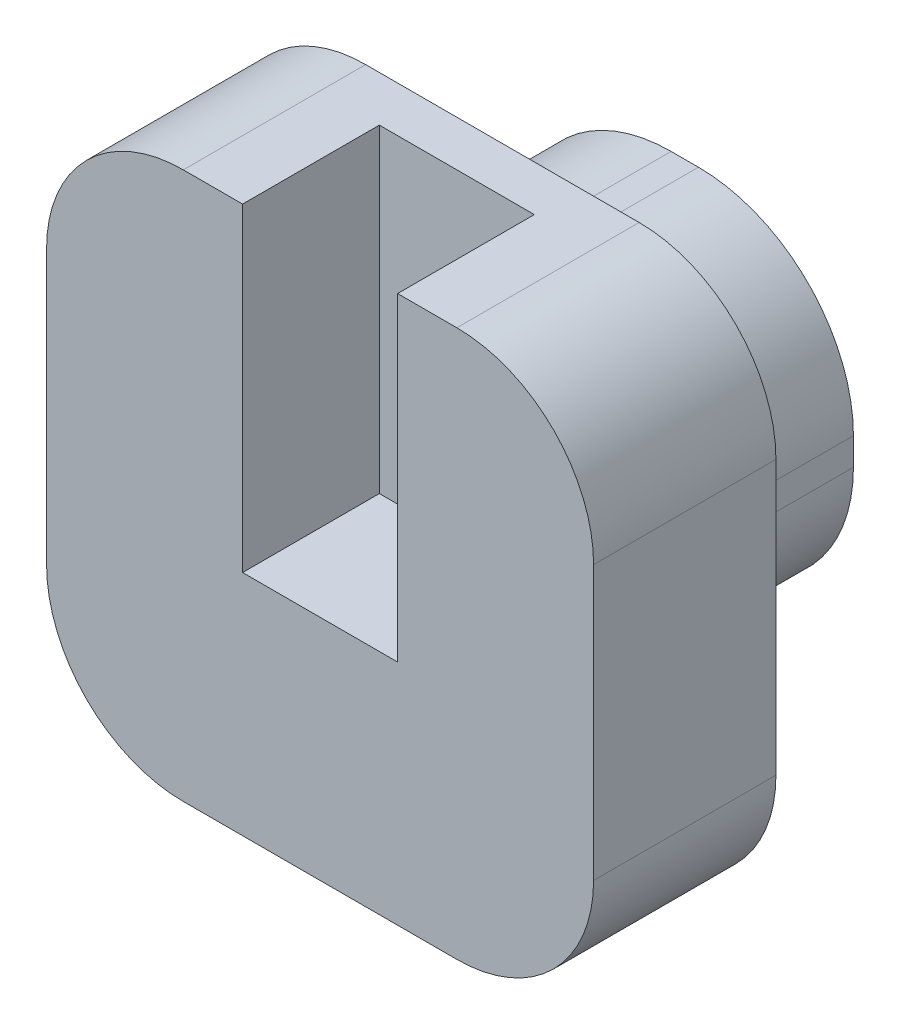
SolidWorks part; units mm, degrees
ref_plane "Спереди" through (0, 0, 0) normal (0, 0, 1) x (1, 0, 0)
ref_plane "Сверху" through (0, 0, 0) normal (0, 1, 0) x (1, 0, 0)
ref_plane "Справа" through (0, 0, 0) normal (1, 0, 0) x (0, 0, -1)
sketch "Эскиз1" plane through (0, 0, 0) normal (0, 0, 1) x (1, 0, 0)
  line L1 (-0.15, -1.85) -> (0.15, -1.85)
  line L2 (-1.85, -0.15) -> (-1.85, 0.15)
  line L3 (-0.15, 1.85) -> (0.15, 1.85)
  line L4 (1.85, -0.15) -> (1.85, 0.15)
  line L5 (-1.85, -1.85) -> (1.85, 1.85) construction
  line L6 (-1.85, 1.85) -> (1.85, -1.85) construction
  arc A0 (-1.85, -0.15) -> (-0.15, -1.85) centre (-0.15, -0.15) ccw
  arc A1 (1.85, 0.15) -> (0.15, 1.85) centre (0.15, 0.15) ccw
  arc A2 (-0.15, 1.85) -> (-1.85, 0.15) centre (-0.15, 0.15) ccw
  arc A3 (1.85, -0.15) -> (0.15, -1.85) centre (0.15, -0.15) cw
  point P0 (0, 0)
  dimension "D3" = 1.7
  dimension "D1" = 3.7
  dimension "D2" = 3.7
extrude "Бобышка-Вытянуть1" add sketch "Эскиз1" along normal blind 2
sketch "Эскиз2" plane through (0, 0, 2) normal (0, 0, 1) x (1, 0, 0)
  line L1 (-1.5, -3) -> (1.5, -3)
  line L2 (-3, -1.5) -> (-3, 1.5)
  line L3 (-1.5, 3) -> (1.5, 3)
  line L4 (3, -1.5) -> (3, 1.5)
  line L5 (-3, -3) -> (3, 3) construction
  line L6 (-3, 3) -> (3, -3) construction
  arc A0 (1.5, -3) -> (3, -1.5) centre (1.5, -1.5) ccw
  arc A1 (-1.5, -3) -> (-3, -1.5) centre (-1.5, -1.5) cw
  arc A2 (3, 1.5) -> (1.5, 3) centre (1.5, 1.5) ccw
  arc A3 (-3, 1.5) -> (-1.5, 3) centre (-1.5, 1.5) cw
  point P0 (0, 0)
  dimension "D3" = 1.5
  dimension "D1" = 6
  dimension "D2" = 6
extrude "Бобышка-Вытянуть2" add sketch "Эскиз2" along normal blind 2 contours A3 L2 A1 L1 A0 L4 A2 L3
sketch "Эскиз4" plane through (0, 3, 0) normal (0, 1, 0) x (1, 0, 0)
  line L0 (3, -4) -> (3, -2) construction
  line L1 (-1.5, -4) -> (1.5, -4) construction
  line L2 (-0.85, -4) -> (0.85, -4)
  line L3 (-0.85, -4) -> (-0.85, -2.5)
  line L4 (-0.85, -2.5) -> (0.85, -2.5)
  line L5 (0.85, -4) -> (0.85, -2.5)
  line L6 (-0.85, -4) -> (0.85, -2.5) construction
  line L7 (-0.85, -2.5) -> (0.85, -4) construction
  point P3 (0, -3.25)
  point P8 (0, -4)
  dimension "D1" = 1.5
  dimension "D2" = 1.7
  dimension "D3" = 3
extrude "Вырез-Вытянуть1" cut sketch "Эскиз4" against normal blind 3.5
equation "\"D3@Эскиз4\"=\"D1@Эскиз2\"/2"
